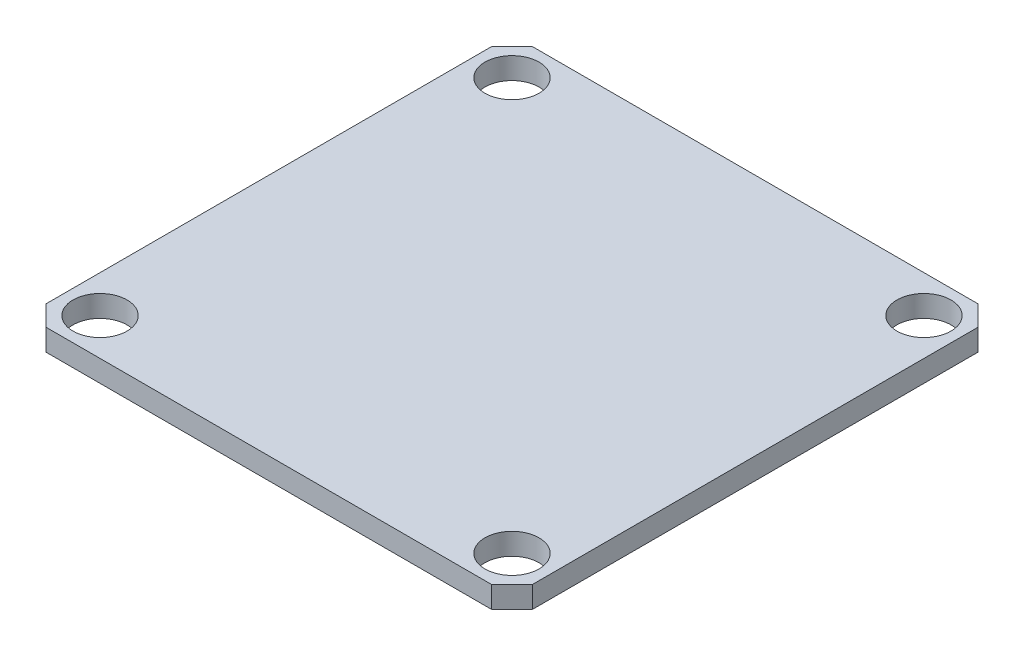
SolidWorks part; units mm, degrees
ref_plane "前视基准面" through (0, 0, 0) normal (0, 0, 1) x (1, 0, 0)
ref_plane "上视基准面" through (0, 0, 0) normal (0, 1, 0) x (1, 0, 0)
ref_plane "右视基准面" through (0, 0, 0) normal (1, 0, 0) x (0, 0, -1)
other "Configuration Table"
sketch "草图1" plane through (0, 0, 0) normal (0, 1, 0) x (1, 0, 0)
  line L0 (-16.5, -18) -> (16.5, -18)
  line L1 (16.5, -18) -> (18, -16.5)
  line L2 (18, -16.5) -> (18, 16.5)
  line L3 (18, 16.5) -> (16.5, 18)
  line L4 (16.5, 18) -> (-16.5, 18)
  line L5 (-16.5, 18) -> (-18, 16.5)
  line L6 (-18, 16.5) -> (-18, -16.5)
  line L7 (-18, -16.5) -> (-16.5, -18)
  line L8 (0, 0) -> (26.8206, 0) construction
  line L9 (0, 0) -> (0, -11.0817) construction
  circle A0 centre (15.25, 15.25) radius 2
  circle A1 centre (-15.25, 15.25) radius 2
  circle A2 centre (15.25, -15.25) radius 2
  circle A3 centre (-15.25, -15.25) radius 2
  dimension "D2" = 4
  dimension "D1" = 33
  dimension "D3" = 15.25
  dimension "D4" = 15.25
extrude "凸台-拉伸1" add sketch "草图1" along normal blind 1.6
